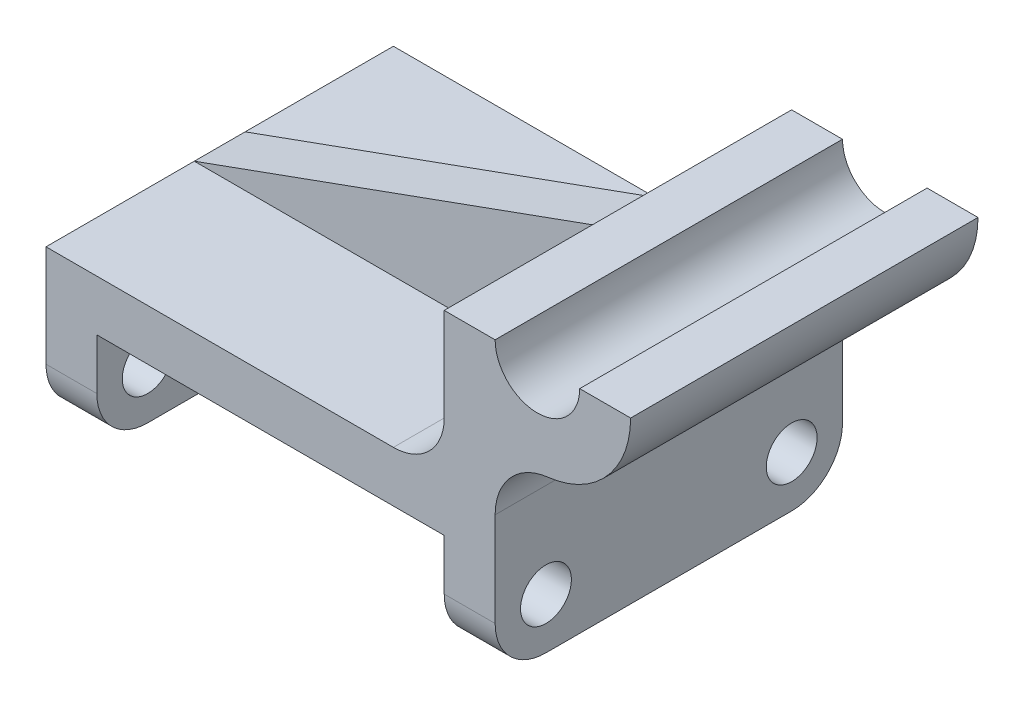
SolidWorks part; units mm, degrees
ref_plane "Ön Düzlem" through (0, 0, 0) normal (0, 0, 1) x (1, 0, 0)
ref_plane "Üst Düzlem" through (0, 0, 0) normal (0, 1, 0) x (1, 0, 0)
ref_plane "Sağ Düzlem" through (0, 0, 0) normal (1, 0, 0) x (0, 0, -1)
sketch "Çizim1" plane through (0, 0, 0) normal (0, 0, 1) x (1, 0, 0)
  line L0 (-78.2134, -40.8385) -> (-66.2134, -40.8385)
  line L1 (-78.2134, -40.8385) -> (-78.2134, -4.8385)
  line L2 (-78.2134, -4.8385) -> (3.7866, -4.8385)
  line L3 (-66.2134, -40.8385) -> (-66.2134, -16.8385)
  line L4 (-66.2134, -16.8385) -> (15.7866, -16.8385)
  line L5 (15.7866, 7.1615) -> (15.7866, 29.1615)
  line L6 (15.7866, -16.8385) -> (15.7866, -40.8385)
  line L7 (15.7866, -40.8385) -> (27.8049, -40.8385)
  line L8 (27.8049, -40.8385) -> (27.8049, -6.6135)
  line L9 (27.8049, 29.1615) -> (15.7866, 29.1615)
  line L11 (47.7683, 29.1615) -> (59.7866, 29.1615)
  arc A0 (27.8049, 29.1615) -> (47.7683, 29.1615) centre (37.7866, 29.1615) ccw
  arc A1 (40.2422, 7.299) -> (59.7866, 29.1615) centre (37.7866, 29.1615) ccw
  arc A2 (40.2422, 7.299) -> (27.8049, -6.6135) centre (41.8049, -6.6135) ccw
  arc A3 (15.7866, 7.1615) -> (3.7866, -4.8385) centre (3.7866, 7.1615) cw
  dimension "D1" = 12
extrude "Yükseklik-Ekstrüzyon1" add sketch "Çizim1" along normal blind 82
fillet "Radyus1" radius 12 4 edges at (21.7958, -40.8385, 82) (21.7958, -40.8385, 0) (-72.2134, -40.8385, 0) (-72.2134, -40.8385, 82)
sketch "Çizim5" plane through (-78.2134, 0, 0) normal (-1, 0, 0) x (0, 0, 1)
  circle A0 centre (12, -28.8385) radius 6
  circle A1 centre (70, -28.8385) radius 6
extrude "Kes-Ekstrüzyon3" cut sketch "Çizim5" against normal blind 107 contours A0 | A1
ref_plane "Düzlem1" through (0, 0, 41) normal (0, 0, 1) x (1, 0, 0)
sketch "Çizim8" plane through (0, 0, 41) normal (0, 0, 1) x (1, 0, 0)
  line L0 (15.7866, 29.1615) -> (15.7866, 7.1615) construction
  line L1 (15.7866, 29.1615) -> (-78.2134, -4.8385)
  line L2 (3.7866, -4.8385) -> (-78.2134, -4.8385) construction
  line L3 (3.7866, -4.8385) -> (-78.2134, -4.8385)
  line L4 (15.7866, 29.1615) -> (15.7866, 7.1615)
  arc A0 (3.7866, -4.8385) -> (15.7866, 7.1615) centre (3.7866, 7.1615) ccw construction
  arc A1 (3.7866, -4.8385) -> (15.7866, 7.1615) centre (3.7866, 7.1615) ccw
extrude "Yükseklik-Ekstrüzyon2" add sketch "Çizim8" along normal blind 6 and the other way blind 6
